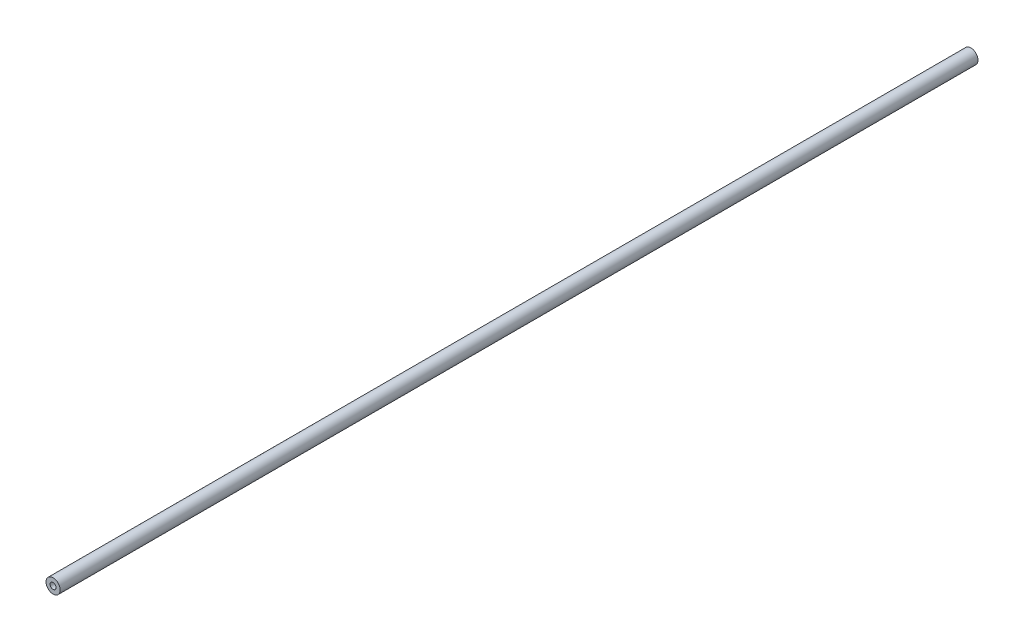
SolidWorks part; units mm, degrees
material "7075-T6, Plate (SS)"
ref_plane "Front Plane" through (0, 0, 0) normal (0, 0, 1) x (1, 0, 0)
ref_plane "Top Plane" through (0, 0, 0) normal (0, 1, 0) x (1, 0, 0)
ref_plane "Right Plane" through (0, 0, 0) normal (1, 0, 0) x (0, 0, -1)
sketch "Sketch1" plane through (0, 0, 0) normal (0, 0, 1) x (1, 0, 0)
  circle A1 centre (0, 0) radius 4.7625
  dimension "D1" = 9.525
extrude "Boss-Extrude1" add sketch "Sketch1" against normal blind 615.95
sketch "Sketch5" plane through (0, 0, -615.95) normal (0, 0, -1) x (-1, 0, 0)
  point P0 (0, 0)
hole_wizard "#10-32 Tapped Hole1" positions "Sketch5" profile "Sketch6" tap size "#10-32" standard "ANSI Inch"
sketch "Sketch6" plane through (0, 0, -615.95) normal (1, 0, 0) x (0, 1, 0)
  line L0 (0, 0) -> (0, 20.2633)
  line L1 (0, 20.2633) -> (2.0193, 19.05)
  line L2 (2.0193, 19.05) -> (2.0193, 0)
  line L5 (2.0193, 0) -> (0, 0)
  line L10 (0, 20.2633) -> (-2.0193, 19.05) construction
  line L11 (0, -6.35) -> (0, 107.95) construction
  dimension "Tap Drill Dia." = 4.0386
  dimension "Tap Drill Depth" = 19.05
  dimension "Drill Angle" = 118
cosmetic thread "Hole Thread1"
hole_wizard "#10-32 Tapped Hole4" positions "Sketch11" profile "Sketch12" tap size "#10-32" standard "ANSI Inch"
sketch "Sketch11" plane through (0, 0, 0) normal (0, 0, 1) x (1, 0, 0)
  point P0 (0, 0)
sketch "Sketch12" plane through (0, 0, 0) normal (1, 0, 0) x (0, -1, 0)
  line L0 (0, 0) -> (0, 20.2633)
  line L1 (0, 20.2633) -> (2.0193, 19.05)
  line L2 (2.0193, 19.05) -> (2.0193, 0)
  line L5 (2.0193, 0) -> (0, 0)
  line L10 (0, 20.2633) -> (-2.0193, 19.05) construction
  line L11 (0, -6.35) -> (0, 107.95) construction
  dimension "Tap Drill Dia." = 4.0386
  dimension "Tap Drill Depth" = 19.05
  dimension "Drill Angle" = 118
cosmetic thread "Hole Thread4"
